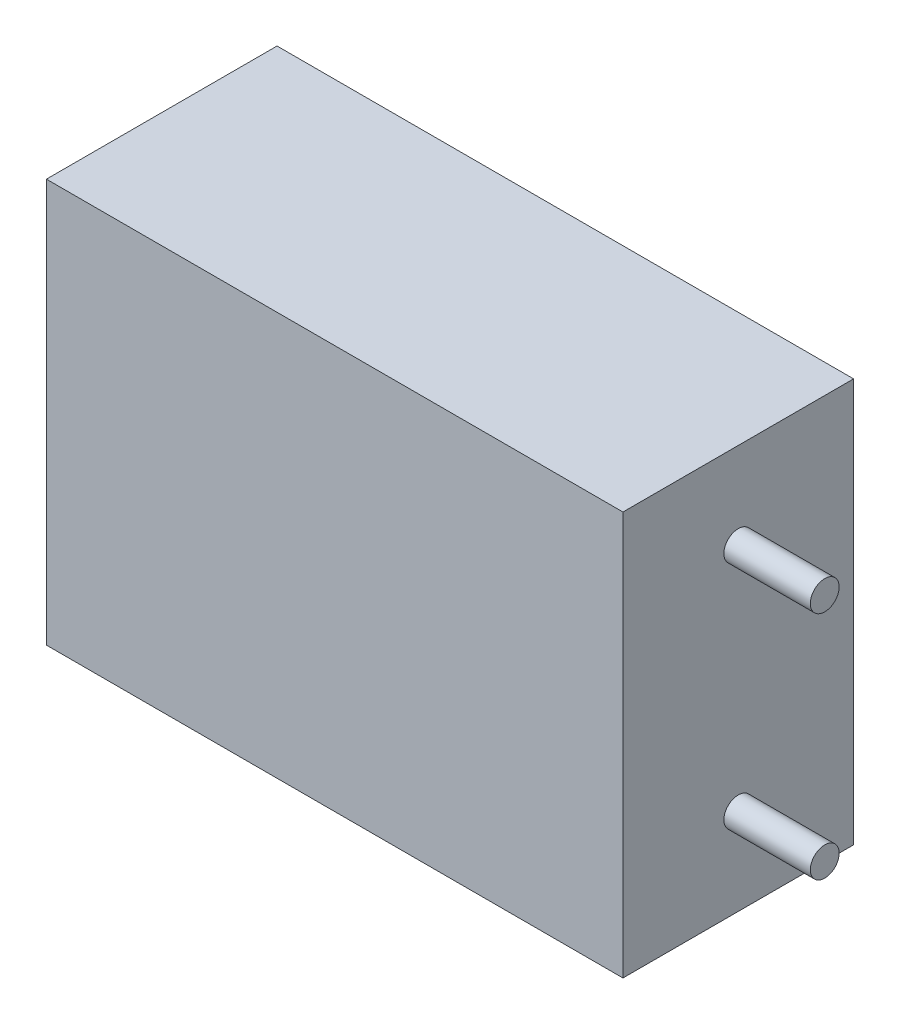
SolidWorks part; units mm, degrees
ref_plane "Front Plane" through (0, 0, 0) normal (0, 0, 1) x (1, 0, 0)
ref_plane "Top Plane" through (0, 0, 0) normal (0, 1, 0) x (1, 0, 0)
ref_plane "Right Plane" through (0, 0, 0) normal (1, 0, 0) x (0, 0, -1)
sketch "Sketch1" plane through (0, 0, 0) normal (0, 1, 0) x (1, 0, 0)
  line L0 (-24.8965, 41.2051) -> (38.6035, 41.2051)
  line L1 (38.6035, 41.2051) -> (38.6035, 15.8051)
  line L2 (38.6035, 15.8051) -> (-24.8965, 15.8051)
  line L3 (-24.8965, 15.8051) -> (-24.8965, 41.2051)
  dimension "D1" = 63.5
  dimension "D2" = 25.4
extrude "Boss-Extrude1" add sketch "Sketch1" along normal blind 44.45
sketch "Sketch2" plane through (38.6035, 0, 0) normal (1, 0, 0) x (0, 0, -1)
  line L0 (41.2051, 44.45) -> (41.2051, 0) construction
  line L1 (15.8051, 44.45) -> (41.2051, 44.45) construction
  line L2 (15.8051, 44.45) -> (15.8051, 0) construction
  line L3 (15.8051, 0) -> (41.2051, 0) construction
  circle A0 centre (28.5051, 34.925) radius 1.5875
  circle A1 centre (28.5051, 9.525) radius 1.5875
  dimension "D3" = 3.175
  dimension "D4" = 3.175
  dimension "D1" = 12.7
  dimension "D2" = 9.525
  dimension "D5" = 12.7
  dimension "D6" = 9.525
extrude "Boss-Extrude2" add sketch "Sketch2" along normal blind 9.525
